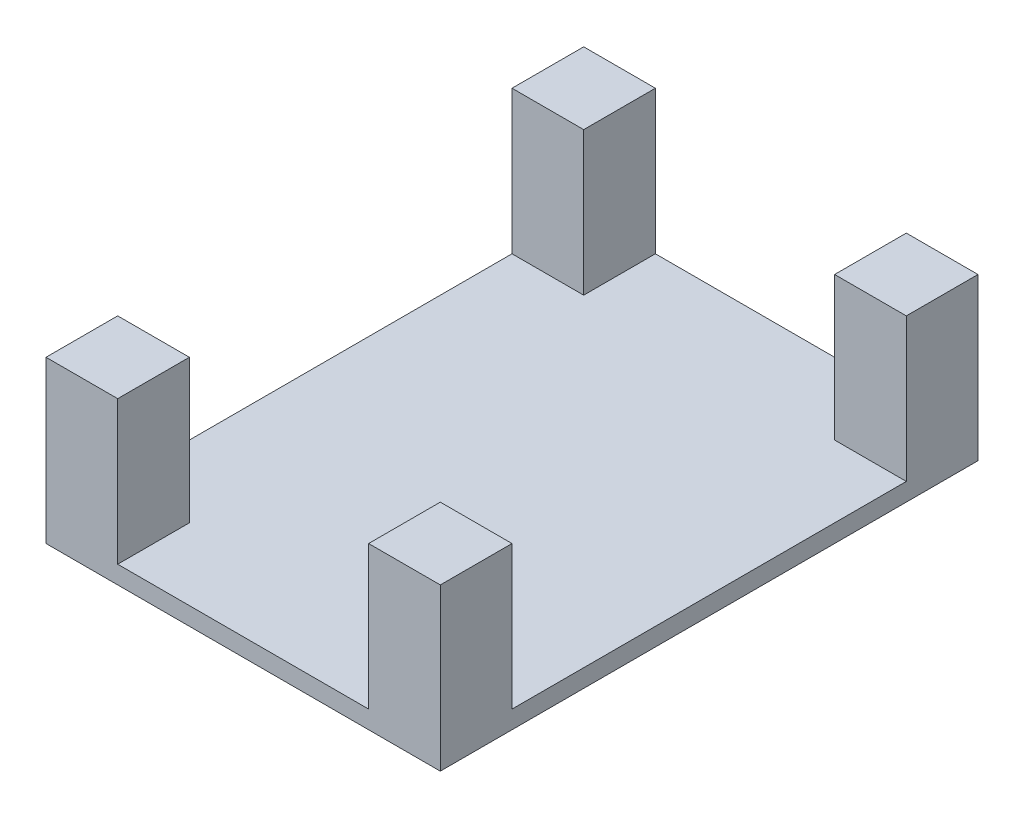
SolidWorks part; units mm, degrees
ref_plane "前视基准面" through (0, 0, 0) normal (0, 0, 1) x (1, 0, 0)
ref_plane "上视基准面" through (0, 0, 0) normal (0, 1, 0) x (1, 0, 0)
ref_plane "右视基准面" through (0, 0, 0) normal (1, 0, 0) x (0, 0, -1)
other "Configuration Table"
sketch "草图2" plane through (0, 0, 0) normal (0, 1, 0) x (1, 0, 0)
  line L1 (0, 0) -> (110, 0)
  line L2 (0, 0) -> (0, 150)
  line L3 (0, 150) -> (110, 150)
  line L4 (110, 0) -> (110, 150)
  dimension "D1" = 150
  dimension "D2" = 110
extrude "凸台-拉伸1" add sketch "草图2" along normal blind 5
sketch "草图3" plane through (0, 5, 0) normal (0, 1, 0) x (1, 0, 0)
  line L0 (0, 75) -> (110, 75) construction
  line L1 (0, 150) -> (20, 150)
  line L2 (0, 150) -> (0, 130)
  line L3 (0, 130) -> (20, 130)
  line L4 (20, 150) -> (20, 130)
  line L5 (0, 150) -> (0, 0) construction
  line L6 (110, 0) -> (110, 150) construction
  line L7 (55, 150) -> (55, 0) construction
  line L8 (110, 150) -> (0, 150) construction
  line L9 (20, 0) -> (20, 20)
  line L10 (0, 20) -> (20, 20)
  line L11 (0, 0) -> (0, 20)
  line L12 (0, 0) -> (20, 0)
  line L13 (110, 0) -> (90, 0)
  line L14 (110, 0) -> (110, 20)
  line L15 (110, 20) -> (90, 20)
  line L16 (90, 0) -> (90, 20)
  line L17 (90, 150) -> (90, 130)
  line L18 (110, 130) -> (90, 130)
  line L19 (110, 150) -> (110, 130)
  line L20 (110, 150) -> (90, 150)
  dimension "D1" = 20
  dimension "D2" = 20
extrude "凸台-拉伸2" add sketch "草图3" along normal blind 40
